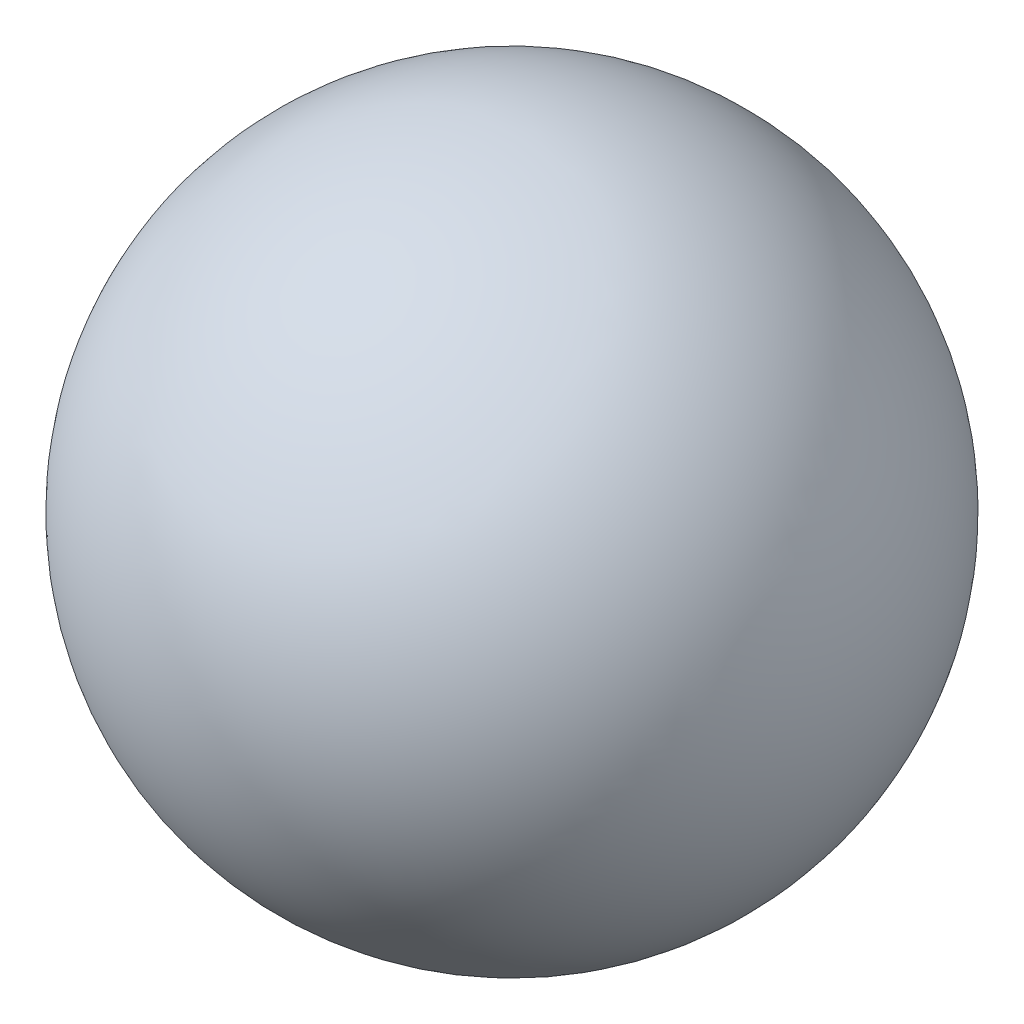
SolidWorks part; units mm, degrees
ref_plane "Front Plane" through (0, 0, 0) normal (0, 0, 1) x (1, 0, 0)
ref_plane "Top Plane" through (0, 0, 0) normal (0, 1, 0) x (1, 0, 0)
ref_plane "Right Plane" through (0, 0, 0) normal (1, 0, 0) x (0, 0, -1)
sketch "Sketch1" plane through (0, 0, 0) normal (0, 0, 1) x (1, 0, 0)
  line L0 (-66.1932, 0) -> (85.2273, 0) construction
  line L1 (-25, 0) -> (25, 0)
  arc A0 (25, 0) -> (-25, 0) centre (0, 0) ccw
  dimension "D1" = 25
revolve "Revolve1" add sketch "Sketch1" angle 360 about L0
